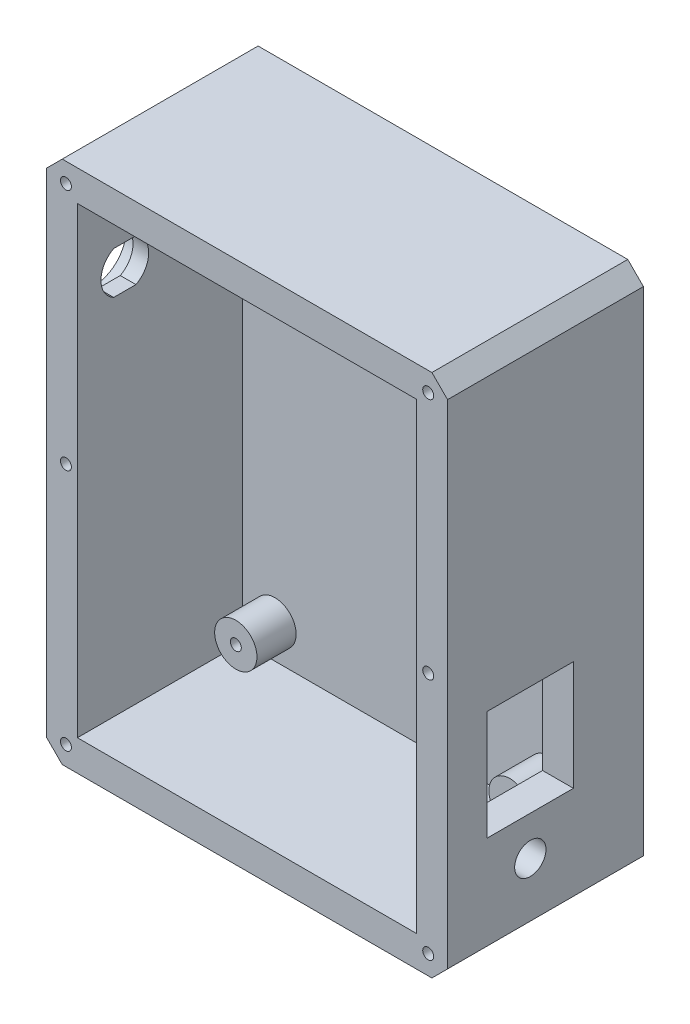
SolidWorks part; units mm, degrees
ref_plane "Front Plane" through (0, 0, 0) normal (0, 0, 1) x (1, 0, 0)
ref_plane "Top Plane" through (0, 0, 0) normal (0, 1, 0) x (1, 0, 0)
ref_plane "Right Plane" through (0, 0, 0) normal (1, 0, 0) x (0, 0, -1)
sketch "Sketch1" plane through (0, 0, 0) normal (0, 0, 1) x (1, 0, 0)
  line L0 (-27.5, 0) -> (27.5, 0) construction
  line L1 (-27.5, -37.5) -> (27.5, -37.5)
  line L2 (-27.5, -37.5) -> (-27.5, 37.5)
  line L3 (-27.5, 37.5) -> (27.5, 37.5)
  line L4 (27.5, -37.5) -> (27.5, 37.5)
  line L5 (-27.5, -37.5) -> (27.5, 37.5) construction
  line L6 (-27.5, 37.5) -> (27.5, -37.5) construction
  line L7 (0, -37.5) -> (0, 37.5) construction
  circle A0 centre (-22.225, 32.004) radius 0.889
  circle A1 centre (-22.225, -32.004) radius 0.889
  circle A2 centre (22.225, -32.004) radius 0.889
  circle A3 centre (22.225, 32.004) radius 0.889
  point P0 (0, 0)
  point P11 (0, 0)
  point P14 (0, 0)
  dimension "D3" = 64.008
  dimension "D5" = 1.778
  dimension "D1" = 55
  dimension "D2" = 75
  dimension "D4" = 44.45
extrude "Boss-Extrude1" add sketch "Sketch1" along normal blind 5
sketch "Sketch2" plane through (0, 0, 0) normal (0, 0, -1) x (-1, 0, 0)
  line L4 (-27.5, 37.5) -> (-27.5, -37.5)
  line L5 (-27.5, -37.5) -> (27.5, -37.5)
  line L6 (27.5, -37.5) -> (27.5, 37.5)
  line L7 (27.5, 37.5) -> (-27.5, 37.5)
  line L8 (-27.5, 37.5) -> (-27.5, -37.5)
  line L9 (-27.5, -37.5) -> (27.5, -37.5)
  line L10 (27.5, -37.5) -> (27.5, 37.5)
  line L11 (27.5, 37.5) -> (-27.5, 37.5)
  line L16 (-32.5, 42.5) -> (-32.5, -42.5)
  line L17 (-32.5, -42.5) -> (32.5, -42.5)
  line L18 (32.5, -42.5) -> (32.5, 42.5)
  line L19 (32.5, 42.5) -> (-32.5, 42.5)
  line L20 (-32.5, 42.5) -> (-32.5, -42.5)
  line L21 (-32.5, -42.5) -> (32.5, -42.5)
  line L22 (32.5, -42.5) -> (32.5, 42.5)
  line L23 (32.5, 42.5) -> (-32.5, 42.5)
  dimension "D1" = 0
  dimension "D2" = 5
extrude "Boss-Extrude2" add sketch "Sketch2" against normal blind 31.75
sketch "Sketch3" plane through (-32.5, 0, 0) normal (-1, 0, 0) x (0, 0, 1)
  line L0 (20.193, 24.8) -> (27.94, 24.8) construction
  line L1 (25.8682, 21.371) -> (22.2648, 21.371)
  line L2 (25.8682, 28.229) -> (22.2648, 28.229)
  line L3 (31.75, -42.5) -> (31.75, 42.5) construction
  line L4 (31.75, 37.5) -> (5, 37.5) construction
  arc A0 (22.2648, 28.229) -> (22.2648, 21.371) centre (24.0665, 24.8) ccw
  arc A1 (25.8682, 21.371) -> (25.8682, 28.229) centre (24.0665, 24.8) ccw
  circle A2 centre (24.0665, 24.8) radius 5.1435 construction
  point P4 (24.0665, 24.8)
  point P9 (29.21, 24.8)
  dimension "D1" = 7.747
  dimension "D3" = 10.287
  dimension "D2" = 6.858
  dimension "D4" = 2.54
  dimension "D5" = 12.7
extrude "Cut-Extrude1" cut sketch "Sketch3" against normal up to next
sketch "Sketch4" plane through (-32.5, 0, 0) normal (-1, 0, 0) x (0, 0, 1)
  arc A0 (22.2648, 28.229) -> (22.2648, 21.371) centre (24.0665, 24.8) ccw construction
  arc A1 (22.2648, 28.229) -> (22.2648, 21.371) centre (24.0665, 24.8) ccw construction
  circle A2 centre (24.0665, 24.8) radius 5.207
  dimension "D1" = 10.414
extrude "Cut-Extrude2" cut sketch "Sketch4" against normal offset from surface (2.46 mm away) 2.54 up to face at (-27.5, 24.8, 24.0665)
chamfer "Chamfer1" distance 2.54 angle 45 4 edges at (-32.5, 42.5, 15.875) (32.5, 42.5, 15.875) (32.5, -42.5, 15.875) (-32.5, -42.5, 15.875)
sketch "Sketch5" plane through (0, 0, 31.75) normal (0, 0, 1) x (1, 0, 0)
  line L0 (27.5, 37.5) -> (31.23, 41.23) construction
  line L1 (32.5, 39.96) -> (29.96, 42.5) construction
  line L2 (0, 0) -> (50000, 0) construction
  line L3 (0, 0) -> (0, -50000) construction
  circle A0 centre (29.365, 39.365) radius 0.889
  circle A1 centre (29.365, -39.365) radius 0.889
  circle A2 centre (-29.365, -39.365) radius 0.889
  circle A3 centre (-29.365, 39.365) radius 0.889
  circle A4 centre (29.365, 0) radius 0.889
  circle A5 centre (-29.365, 0) radius 0.889
  point P20 (29.8242, 0)
  dimension "D1" = 1.778
extrude "Cut-Extrude3" cut sketch "Sketch5" against normal blind 19.05
sketch "Sketch6" plane through (0, 0, 5) normal (0, 0, 1) x (1, 0, 0)
  circle A0 centre (-22.225, 32.004) radius 0.889 construction
  circle A1 centre (-22.225, -32.004) radius 0.889 construction
  circle A2 centre (22.225, -32.004) radius 0.889 construction
  circle A3 centre (22.225, 32.004) radius 0.889 construction
  circle A4 centre (-22.225, 32.004) radius 0.889
  circle A5 centre (-22.225, -32.004) radius 0.889
  circle A6 centre (22.225, -32.004) radius 0.889
  circle A7 centre (22.225, 32.004) radius 0.889
  circle A8 centre (-22.225, 32.004) radius 3.429
  circle A9 centre (-22.225, -32.004) radius 3.429
  circle A10 centre (22.225, -32.004) radius 3.429
  circle A11 centre (22.225, 32.004) radius 3.429
  dimension "D1" = 2.54
extrude "Boss-Extrude3" add sketch "Sketch6" along normal blind 6.35
sketch "Sketch7" plane through (32.5, 0, 0) normal (1, 0, 0) x (0, 0, -1)
  line L0 (-11.35, -28.575) -> (-11.35, -35.433) construction
  line L1 (-25.32, -24.8) -> (-11.35, -24.8)
  line L2 (-25.32, -24.8) -> (-25.32, -7.02)
  line L3 (-25.32, -7.02) -> (-11.35, -7.02)
  line L4 (-11.35, -24.8) -> (-11.35, -7.02)
  line L5 (-25.32, -24.8) -> (-11.35, -7.02) construction
  line L6 (-25.32, -7.02) -> (-11.35, -24.8) construction
  line L7 (-31.75, -37.5) -> (-5, -37.5) construction
  point P0 (-18.335, -15.91)
  point P5 (-18.5749, -13.5622)
  dimension "D1" = 17.78
  dimension "D2" = 13.97
  dimension "D3" = 12.7
extrude "Cut-Extrude4" cut sketch "Sketch7" against normal up to next
sketch "Sketch8" plane through (32.5, 0, 0) normal (1, 0, 0) x (0, 0, -1)
  line L0 (-25.32, -24.8) -> (-11.35, -24.8) construction
  circle A0 centre (-18.335, -31.15) radius 2.54
  point P4 (-18.335, -24.8)
  dimension "D1" = 5.08
  dimension "D2" = 6.35
extrude "Cut-Extrude5" cut sketch "Sketch8" against normal up to next
